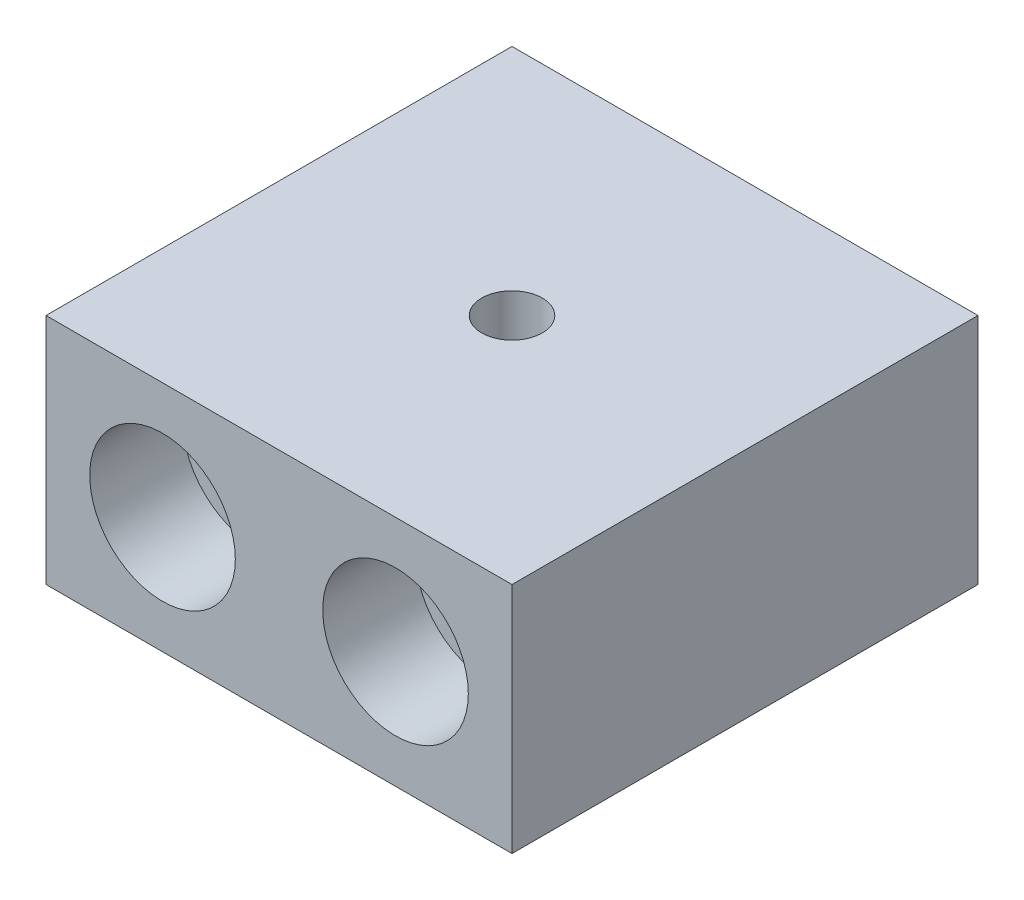
SolidWorks part; units mm, degrees
material "6061 Alloy"
ref_plane "Front" through (0, 0, 0) normal (0, 0, 1) x (1, 0, 0)
ref_plane "Top" through (0, 0, 0) normal (0, 1, 0) x (1, 0, 0)
ref_plane "Right" through (0, 0, 0) normal (1, 0, 0) x (0, 0, -1)
sketch "Sketch1" plane through (0, 0, 0) normal (0, 0, 1) x (1, 0, 0)
  line L1 (-12.7, -6.35) -> (12.7, -6.35)
  line L2 (-12.7, -6.35) -> (-12.7, 6.35)
  line L3 (-12.7, 6.35) -> (12.7, 6.35)
  line L4 (12.7, -6.35) -> (12.7, 6.35)
  line L5 (-12.7, -6.35) -> (12.7, 6.35) construction
  line L6 (-12.7, 6.35) -> (12.7, -6.35) construction
  point P0 (0, 0)
  dimension "D1" = 12.7
  dimension "D2" = 25.4
extrude "Boss-Extrude1" add sketch "Sketch1" along normal mid plane 25.4
hole_wizard "CBORE for #8 Socket Head Cap Screw1" positions "Sketch2" profile "Sketch3" counterbore size "#8" standard "ANSI Inch" end condition up to next
sketch "Sketch2" plane through (0, 0, 12.7) normal (0, 0, 1) x (1, 0, 0)
  line L0 (6.35, 0) -> (-6.35, 0) construction
  line L2 (-12.7, -6.35) -> (12.7, -6.35) construction
  line L3 (12.7, -6.35) -> (12.7, 6.35) construction
  point P0 (-6.35, 0)
  point P2 (6.35, 0)
  dimension "D1" = 12.7
  dimension "D2" = 6.35
  dimension "D3" = 6.35
sketch "Sketch3" plane through (-6.35, 0, 12.7) normal (1, 0, 0) x (0, -1, 0)
  line L0 (0, 0) -> (0, 25.4)
  line L1 (0, 25.4) -> (2.4574, 25.4)
  line L3 (2.4574, 25.4) -> (2.4575, 5.08)
  line L4 (2.4575, 5.08) -> (3.9687, 5.08)
  line L5 (3.9687, 5.08) -> (3.9688, 0)
  line L7 (3.9688, 0) -> (0, 0)
  line L11 (0, -6.35) -> (0, 107.95) construction
  dimension "Thru Hole Dia." = 4.9149
  dimension "Thru Hole Depth" = 25.4
  dimension "C'Bore Dia." = 7.9375
  dimension "C'Bore Depth" = 5.08
hole_wizard "M4x0.7 Tapped Hole1" positions "Sketch4" profile "Sketch5" tap size "M4x0.7" standard "ANSI Metric"
sketch "Sketch4" plane through (0, 6.35, 0) normal (0, 1, 0) x (1, 0, 0)
  point P10 (0, 0)
cosmetic thread "Hole Thread1" parameters "D1"=9.525, "D2"=4
sketch "Sketch5" plane through (0, 6.35, 0) normal (1, 0, 0) x (0, 0, 1)
  line L0 (0, 0) -> (0, 12.6246)
  line L1 (0, 12.6246) -> (1.65, 11.6332)
  line L2 (1.65, 11.6332) -> (1.65, 0)
  line L5 (1.65, 0) -> (0, 0)
  line L10 (0, 12.6246) -> (-1.65, 11.6332) construction
  line L11 (0, -6.35) -> (0, 107.95) construction
  dimension "Tap Drill Dia." = 3.3
  dimension "Tap Drill Depth" = 11.6332
  dimension "Drill Angle" = 118
